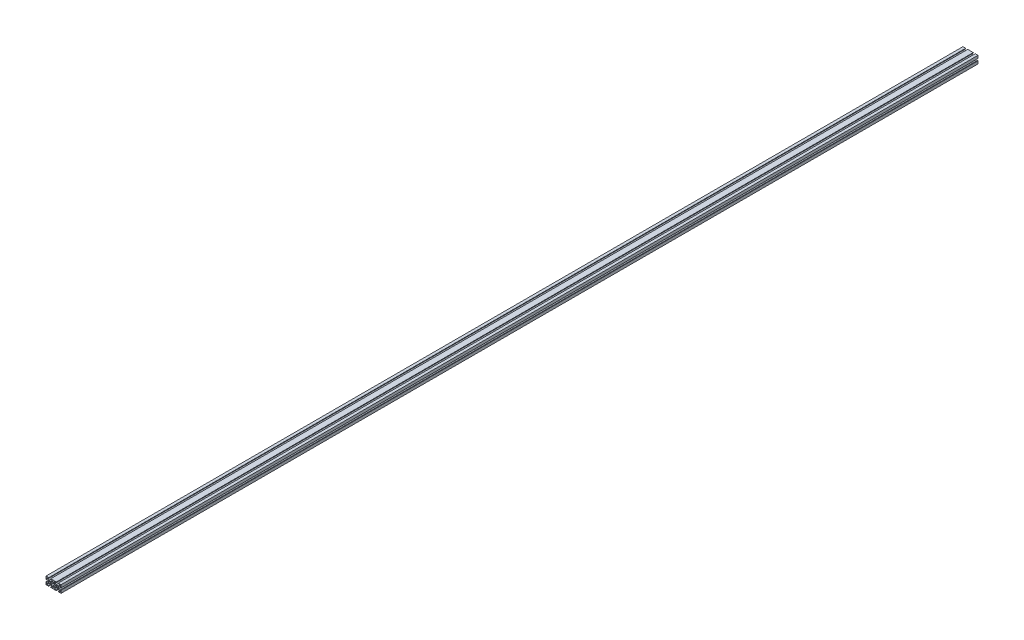
SolidWorks part; units mm, degrees
material "6063-T5"
ref_plane "Front Plane" through (0, 0, 0) normal (0, 0, 1) x (1, 0, 0)
ref_plane "Top Plane" through (0, 0, 0) normal (0, 1, 0) x (1, 0, 0)
ref_plane "Right Plane" through (0, 0, 0) normal (1, 0, 0) x (0, 0, -1)
sketch "Sketch1" plane through (0, 0, 0) normal (0, 0, 1) x (1, 0, 0)
  line L0 (0, 20) -> (20, 0) construction
  line L1 (0, 0) -> (20, 0) construction
  line L2 (0, 0) -> (0, 20) construction
  line L3 (0, 20) -> (20, 20) construction
  line L4 (20, 0) -> (20, 20) construction
  line L5 (20, 20) -> (0, 0) construction
  line L6 (18.5, 1.5) -> (18.5, 0) construction
  line L7 (1.5, 1.5) -> (18.5, 1.5) construction
  line L8 (1.5, 1.5) -> (1.5, 18.5) construction
  line L9 (1.5, 18.5) -> (18.5, 18.5) construction
  line L10 (18.5, 1.5) -> (18.5, 18.5) construction
  line L11 (18.5, 1.5) -> (20, 1.5) construction
  line L12 (6.345, 12.5943) -> (1.5, 17.4393)
  line L13 (13.655, 6.345) -> (6.345, 6.345) construction
  line L14 (13.655, 6.345) -> (13.655, 13.655) construction
  line L15 (13.655, 13.655) -> (6.345, 13.655) construction
  line L16 (6.345, 6.345) -> (6.345, 13.655) construction
  line L17 (7.4057, 13.655) -> (2.5607, 18.5)
  line L18 (2.5607, 18.5) -> (2.0303, 17.9697) construction
  line L19 (2.0303, 17.9697) -> (1.5, 17.4393) construction
  line L20 (6.345, 7.4057) -> (6.345, 12.5943)
  line L21 (12.5943, 13.655) -> (17.4393, 18.5)
  line L22 (17.4393, 18.5) -> (17.9697, 17.9697) construction
  line L23 (17.9697, 17.9697) -> (18.5, 17.4393) construction
  line L24 (18.5, 17.4393) -> (13.655, 12.5943)
  line L25 (13.655, 7.4057) -> (18.5, 2.5607)
  line L26 (18.5, 2.5607) -> (17.9697, 2.0303) construction
  line L27 (17.4393, 1.5) -> (12.5943, 6.345)
  line L28 (7.4057, 6.345) -> (2.5607, 1.5)
  line L29 (17.9697, 2.0303) -> (17.4393, 1.5) construction
  line L30 (1.5, 2.5607) -> (6.345, 7.4057)
  line L31 (2.5607, 1.5) -> (2.0303, 2.0303) construction
  line L32 (2.0303, 2.0303) -> (1.5, 2.5607) construction
  line L33 (7.4057, 13.655) -> (12.5943, 13.655)
  line L34 (13.655, 12.5943) -> (13.655, 7.4057)
  line L36 (12.5943, 6.345) -> (7.4057, 6.345)
  line L37 (0, 10) -> (1.5, 10) construction
  line L38 (0.75, 12.63) -> (0.75, 10) construction
  line L39 (0.75, 10) -> (0.75, 7.37) construction
  line L40 (1.5, 12.63) -> (0, 12.63)
  line L41 (1.5, 7.37) -> (0, 7.37)
  line L42 (10, 1.5) -> (10, 0) construction
  line L43 (10, 0.75) -> (12.63, 0.75) construction
  line L44 (10, 0.75) -> (7.37, 0.75) construction
  line L45 (12.63, 0) -> (12.63, 1.5)
  line L46 (7.37, 1.5) -> (7.37, 0)
  line L47 (18.5, 12.63) -> (20, 12.63)
  line L48 (18.5, 7.37) -> (20, 7.37)
  line L49 (7.37, 20) -> (7.37, 18.5)
  line L50 (12.63, 20) -> (12.63, 18.5)
  line L51 (2.5607, 1.5) -> (7.37, 1.5)
  line L52 (12.63, 1.5) -> (17.4393, 1.5)
  line L53 (18.5, 7.37) -> (18.5, 2.5607)
  line L54 (18.5, 12.63) -> (18.5, 17.4393)
  line L55 (17.4393, 18.5) -> (12.63, 18.5)
  line L56 (7.37, 18.5) -> (2.5607, 18.5)
  line L57 (1.5, 17.4393) -> (1.5, 12.63)
  line L58 (1.5, 7.37) -> (1.5, 2.5607)
  line L59 (7.37, 0) -> (0, 0)
  line L60 (0, 0) -> (0, 7.37)
  line L61 (0, 12.63) -> (0, 20)
  line L62 (0, 20) -> (7.37, 20)
  line L63 (12.63, 20) -> (20, 20)
  line L64 (20, 20) -> (20, 12.63)
  line L65 (20, 7.37) -> (20, 0)
  line L66 (20, 0) -> (12.63, 0)
  circle A0 centre (10, 10) radius 2.095
  dimension "D2" = 4.19
  dimension "D6" = 5.26
  dimension "D1" = 20
  dimension "D3" = 1.5
  dimension "D4" = 3.655
  dimension "D5" = 1.5
extrude "Boss-Extrude1" add sketch "Sketch1" along normal blind 2440
pattern_linear "LPattern1" count 2 spacing 20 along (1, 0, 0) of "Boss-Extrude1"
